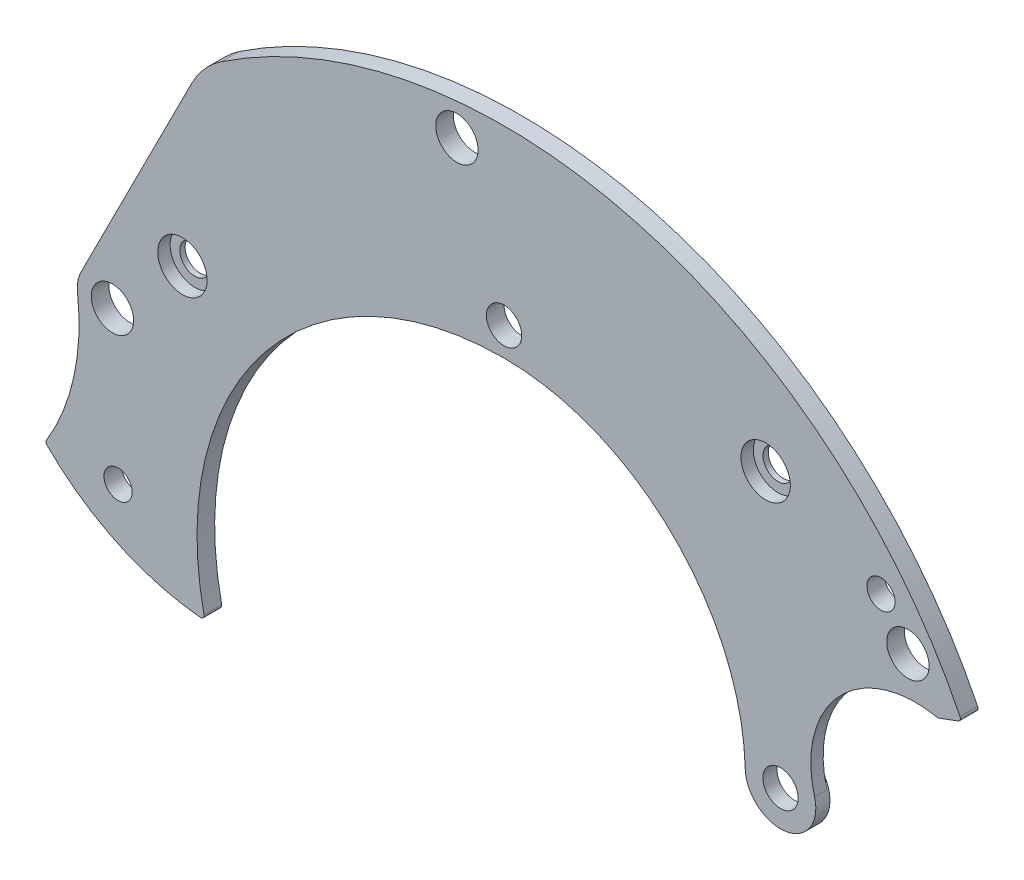
SolidWorks part; units mm, degrees
material "Латунь"
ref_plane "Спереди" through (0, 0, 0) normal (0, 0, 1) x (1, 0, 0)
ref_plane "Сверху" through (0, 0, 0) normal (0, 1, 0) x (1, 0, 0)
ref_plane "Справа" through (0, 0, 0) normal (1, 0, 0) x (0, 0, -1)
other "Configuration Table"
sketch "Эскиз1" plane through (0, 0, 0) normal (0, 0, 1) x (1, 0, 0)
  line L5 (0, 8.7) -> (-4.7186, 8.7) construction
  line L8 (12.9662, 6.264) -> (12.291, 6.0145)
  line L9 (-8.8495, 11.0181) -> (-11.9848, 4.8213)
  circle A2 centre (7.8326, 2.0642) radius 0.5
  circle A3 centre (0, 9.5) radius 0.5
  arc A5 (6.8329, 2.0388) -> (8.7967, 2.3298) centre (7.8326, 2.0642) ccw
  arc A6 (12.9662, 6.264) -> (-8.0093, 11.9671) centre (0, 0) ccw
  circle A7 centre (-10.9359, 0.1356) radius 0.4
  circle A8 centre (-9.1125, 6.4014) radius 0.425
  circle A9 centre (7.4113, 9.6267) radius 0.425
  circle A10 centre (10.6793, 8.251) radius 0.4
  arc A11 (12.291, 6.0145) -> (8.7967, 2.3298) centre (11.656, 3.1174) ccw
  arc A12 (0, 8.7) -> (6.8329, 2.0388) centre (0, 1.8649) cw
  arc A13 (0, 8.7) -> (-8.4718, -1.9797) centre (0, 0) ccw
  arc A14 (-8.0093, 11.9671) -> (-8.8495, 11.0181) centre (-6.6188, 9.8895) ccw
  arc A15 (-13.0047, 0.1411) -> (-12.0852, 4.2546) centre (-18.4078, 3.5083) ccw
  arc A16 (-13.0047, 0.1411) -> (-8.4718, -1.9797) centre (-7.9073, 5.1316) ccw
  arc A17 (-11.9848, 4.8213) -> (-12.0852, 4.2546) centre (-11.0956, 4.3714) ccw
  dimension "D1" = 2.5
  dimension "D2" = 1
  dimension "D3" = 1
  dimension "D4" = 14.4
  dimension "D5" = 0.8
  dimension "D6" = 0.85
  dimension "D7" = 8.7
extrude "Бобышка-Вытянуть1" add sketch "Эскиз1" along normal blind 0.5
sketch "Эскиз2" plane through (0, 0, 0) normal (0, 0, -1) x (-1, 0, 0)
  circle A0 centre (-7.8326, 2.0642) radius 4.472
  dimension "D1" = 8.944
extrude "Вырез-Вытянуть1" cut sketch "Эскиз2" against normal blind 0.1
sketch "Эскиз3" plane through (0, 0, 0.5) normal (0, 0, 1) x (1, 0, 0)
  circle A0 centre (-9.1125, 6.4014) radius 0.7
  circle A1 centre (7.4113, 9.6267) radius 0.7
  dimension "D1" = 1.4
extrude "Вырез-Вытянуть2" cut sketch "Эскиз3" against normal blind 0.35
sketch "Эскиз4" plane through (0, 0, 0.1) normal (0, 0, -1) x (-1, 0, 0)
  circle A0 centre (-7.8326, 2.0642) radius 4.472
  circle A1 centre (-7.8326, 2.0642) radius 1
  arc A2 (-8.7967, 2.3298) -> (-6.8329, 2.0388) centre (-7.8326, 2.0642) ccw construction
extrude "Вырез-Вытянуть3" cut sketch "Эскиз4" against normal blind 0.05
fillet "Скругление1" radius 0.1 6 edges at (5.522, 5.8931, 0.075) (10.3331, 5.7718, 0.075) (12.9662, 6.264, 0.25) (12.291, 6.0145, 0.25) (-13.0047, 0.1411, 0.25) (-8.4718, -1.9797, 0.25)
sketch "Эскиз5" plane through (0, 0, 0.5) normal (0, 0, 1) x (1, 0, 0)
  line L0 (-11.0956, 4.3714) -> (-1.3362, 13.4337) construction
  line L1 (-1.3362, 13.4337) -> (11.4423, 7.164) construction
  circle A0 centre (0, 0) radius 13.5 construction
  circle A1 centre (-11.0956, 4.3714) radius 0.6
  circle A2 centre (11.4423, 7.164) radius 0.6
  circle A3 centre (-1.3362, 13.4337) radius 0.6
  dimension "D1" = 1.2
  dimension "D2" = 27
extrude "Вырез-Вытянуть4" cut sketch "Эскиз5" against normal blind 10
